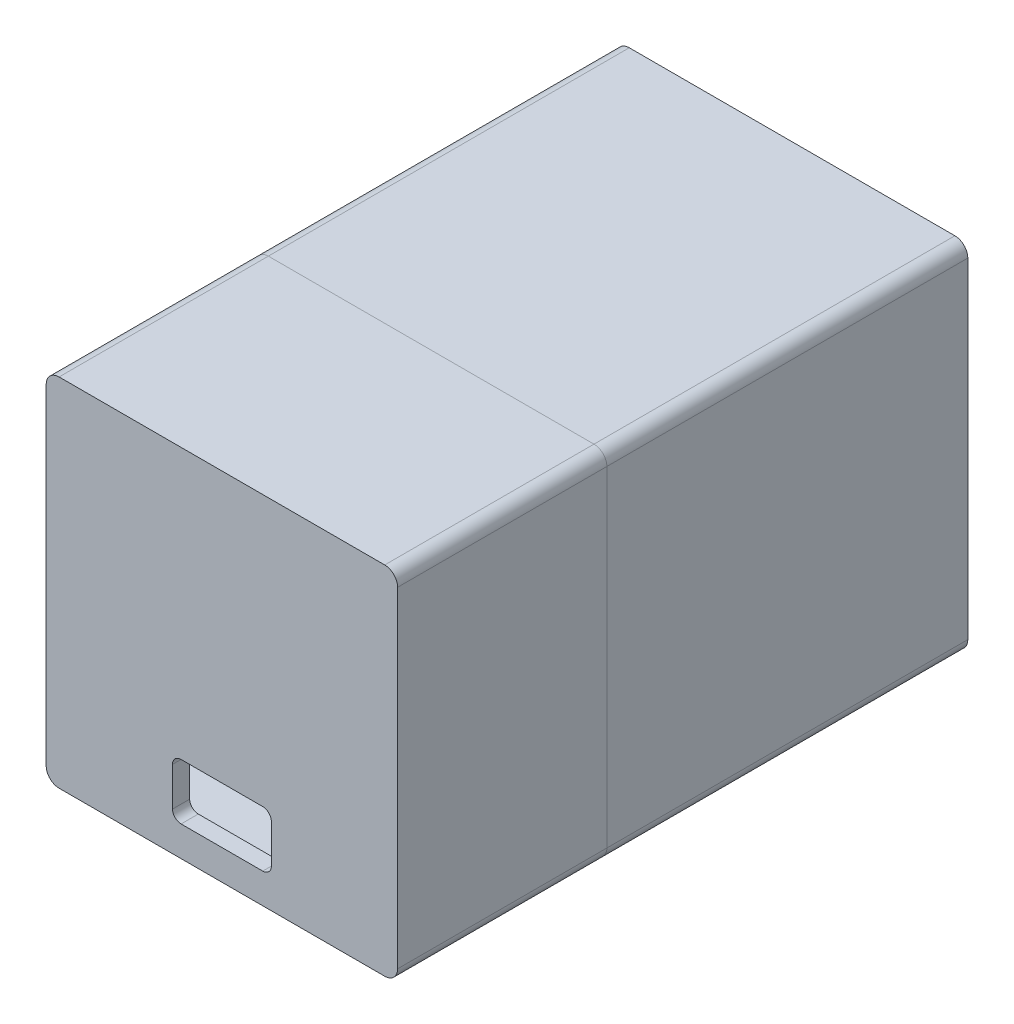
SolidWorks part; units mm, degrees
material "Custom Plastic"
ref_plane "X-Y Datum" through (0, 0, 0) normal (0, 0, 1) x (1, 0, 0)
ref_plane "X-Z Datum" through (0, 0, 0) normal (0, 1, 0) x (1, 0, 0)
ref_plane "Y-Z Datum" through (0, 0, 0) normal (1, 0, 0) x (0, 0, -1)
sketch "Sketch1" plane through (0, 0, 0) normal (0, 0, 1) x (1, 0, 0)
  line L0 (-36.8935, 36.449) -> (-36.8935, -36.449)
  line L1 (-36.5125, 36.068) -> (36.5125, 36.068) construction
  line L2 (-36.5125, 36.068) -> (-36.5125, -36.068) construction
  line L3 (-36.5125, -36.068) -> (36.5125, -36.068) construction
  line L4 (36.5125, 36.068) -> (36.5125, -36.068) construction
  line L5 (-36.5125, 36.068) -> (36.5125, -36.068) construction
  line L6 (-36.5125, -36.068) -> (36.5125, 36.068) construction
  line L7 (-36.8935, -36.449) -> (36.8935, -36.449)
  line L8 (36.8935, 36.449) -> (36.8935, -36.449)
  line L9 (-36.8935, 36.449) -> (36.8935, 36.449)
  point P0 (0, 0)
  dimension "D1" = 73.025
  dimension "D2" = 72.136
  dimension "D3" = 0.381
extrude "Boss-Extrude1" add sketch "Sketch1" along normal blind 123.698
shell "Shell1" thickness 4
sketch "Sketch2" plane through (0, 0, 123.698) normal (0, 0, 1) x (1, 0, 0)
  line L1 (36.8935, 36.449) -> (-36.8935, 36.449) construction
  line L2 (-36.8935, 36.449) -> (-36.8935, -36.449) construction
  line L3 (-36.8935, -36.449) -> (36.8935, -36.449) construction
  line L4 (40.8935, 40.449) -> (-40.8935, 40.449)
  line L5 (-40.8935, 40.449) -> (-40.8935, -40.449)
  line L6 (-40.8935, -40.449) -> (40.8935, -40.449)
  line L7 (40.8935, -40.449) -> (40.8935, 40.449)
  line L8 (40.8935, 40.449) -> (-40.8935, 40.449)
  line L9 (-40.8935, 40.449) -> (-40.8935, -40.449)
  line L10 (-40.8935, -40.449) -> (40.8935, -40.449)
  line L11 (40.8935, -40.449) -> (40.8935, 40.449)
  line L12 (36.8935, -36.449) -> (36.8935, 36.449) construction
  line L13 (36.8935, 36.449) -> (-36.8935, 36.449)
  line L14 (-36.8935, 36.449) -> (-36.8935, -36.449)
  line L15 (-36.8935, -36.449) -> (36.8935, -36.449)
  line L16 (36.8935, -36.449) -> (36.8935, 36.449)
  dimension "D1" = 0
extrude "Boss-Extrude2" add sketch "Sketch2" along normal blind 1
sketch "Sketch7" plane through (0, 0, 124.698) normal (0, 0, 1) x (1, 0, 0)
  line L4 (40.8935, -40.449) -> (40.8935, 40.449)
  line L5 (40.8935, 40.449) -> (-40.8935, 40.449)
  line L6 (-40.8935, 40.449) -> (-40.8935, -40.449)
  line L7 (-40.8935, -40.449) -> (40.8935, -40.449)
  line L8 (40.8935, -40.449) -> (40.8935, 40.449)
  line L9 (40.8935, 40.449) -> (-40.8935, 40.449)
  line L10 (-40.8935, 40.449) -> (-40.8935, -40.449)
  line L11 (-40.8935, -40.449) -> (40.8935, -40.449)
  dimension "D1" = 0
extrude "Boss-Extrude5" add sketch "Sketch7" along normal blind 4
sketch "Sketch3" plane through (0, -40.449, 0) normal (0, -1, 0) x (1, 0, 0)
  line L4 (-40.8935, -4) -> (40.8935, -4)
  line L5 (40.8935, -4) -> (40.8935, 128.698)
  line L6 (40.8935, 128.698) -> (-40.8935, 128.698)
  line L7 (-40.8935, 128.698) -> (-40.8935, -4)
  line L8 (-40.8935, -4) -> (40.8935, -4)
  line L9 (40.8935, -4) -> (40.8935, 128.698)
  line L11 (-40.8935, 128.698) -> (-40.8935, -4)
  line L12 (40.8935, 128.698) -> (-40.8935, 128.698)
  dimension "D1" = 0
extrude "Boss-Extrude3" add sketch "Sketch3" along normal blind 2
sketch "Sketch4" plane through (0, -42.449, 0) normal (0, -1, 0) x (1, 0, 0)
  circle A0 centre (-22.225, 109.648) radius 3.025
  circle A1 centre (22.225, 109.648) radius 3.025
  circle A2 centre (-22.225, 15.05) radius 3.025
  circle A3 centre (22.225, 15.05) radius 3.025
  dimension "D1" = 6.05
extrude "Cut-Extrude2" cut sketch "Sketch4" against normal blind 5
fillet "Fillet1" radius 3 4 edges at (-40.8935, 40.449, 62.349) (-40.8935, -42.449, 62.349) (40.8935, 40.449, 62.349) (40.8935, -42.449, 62.349)
ref_plane "Plane1" through (0, 0, 80) normal (0, 0, 1) x (1, 0, 0)
split "Split1" trim tools "Plane1" bodies to split 104 resulting bodies 105 106
sketch "Sketch5" plane through (0, 0, 80) normal (0, 0, 1) x (1, 0, 0)
  line L0 (-38.8935, 38.449) -> (-38.8935, -38.449)
  line L1 (-38.8935, -38.449) -> (38.8935, -38.449)
  line L2 (38.8935, -38.449) -> (38.8935, 38.449)
  line L3 (38.8935, 38.449) -> (-38.8935, 38.449)
  line L4 (36.8935, 36.449) -> (-36.8935, 36.449)
  line L5 (-36.8935, 36.449) -> (-36.8935, -36.449)
  line L6 (-36.8935, -36.449) -> (36.8935, -36.449)
  line L7 (36.8935, -36.449) -> (36.8935, 36.449)
  line L8 (36.8935, 36.449) -> (-36.8935, 36.449)
  line L9 (-36.8935, 36.449) -> (-36.8935, -36.449)
  line L10 (-36.8935, -36.449) -> (36.8935, -36.449)
  line L11 (36.8935, -36.449) -> (36.8935, 36.449)
  dimension "D1" = 0
  dimension "D2" = 2
extrude "Boss-Extrude4" add sketch "Sketch5" along normal blind 20
sketch "Sketch6" plane through (0, 0, 80) normal (0, 0, -1) x (-1, 0, 0)
  line L4 (-38.8935, 38.449) -> (-38.8935, -38.449) construction
  line L5 (-38.8935, -38.449) -> (38.8935, -38.449) construction
  line L6 (38.8935, -38.449) -> (38.8935, 38.449) construction
  line L7 (38.8935, 38.449) -> (-38.8935, 38.449) construction
  line L16 (36.8935, 36.449) -> (-36.8935, 36.449)
  line L17 (-36.8935, 36.449) -> (-36.8935, -36.449)
  line L18 (-36.8935, -36.449) -> (36.8935, -36.449)
  line L19 (36.8935, -36.449) -> (36.8935, 36.449)
  line L20 (36.8935, 36.449) -> (-36.8935, 36.449) construction
  line L21 (-36.8935, 36.449) -> (-36.8935, -36.449) construction
  line L22 (-36.8935, -36.449) -> (36.8935, -36.449) construction
  line L23 (36.8935, -36.449) -> (36.8935, 36.449) construction
  line L24 (-39.0435, 38.599) -> (-39.0435, -38.599)
  line L25 (-39.0435, -38.599) -> (39.0435, -38.599)
  line L26 (39.0435, -38.599) -> (39.0435, 38.599)
  line L27 (39.0435, 38.599) -> (-39.0435, 38.599)
  dimension "D1" = 0
  dimension "D2" = 2
  dimension "D3" = 0.15
extrude "Cut-Extrude3" cut sketch "Sketch6" against normal blind 21
other "Save Bodies1"
sketch "Sketch8" plane through (0, 0, 128.698) normal (0, 0, 1) x (1, 0, 0)
  line L0 (0, 40.449) -> (0, -42.449) construction
  line L1 (37.8935, 40.449) -> (-37.8935, 40.449) construction
  line L2 (37.8935, -42.449) -> (-37.8935, -42.449) construction
  line L4 (-11.5, -22.449) -> (11.5, -22.449)
  line L5 (-11.5, -22.449) -> (-11.5, -35.449)
  line L6 (-11.5, -35.449) -> (11.5, -35.449)
  line L7 (11.5, -22.449) -> (11.5, -35.449)
  line L8 (-11.5, -22.449) -> (11.5, -35.449) construction
  line L9 (-11.5, -35.449) -> (11.5, -22.449) construction
  point P6 (0, -28.949)
  dimension "D1" = 13
  dimension "D2" = 23
  dimension "D3" = 7
extrude "Cut-Extrude4" cut sketch "Sketch8" against normal blind 10
fillet "Fillet2" radius 2 4 edges at (-11.5, -22.449, 126.698) (11.5, -22.449, 126.698) (11.5, -35.449, 126.698) (-11.5, -35.449, 126.698)
other "Save Bodies2"
